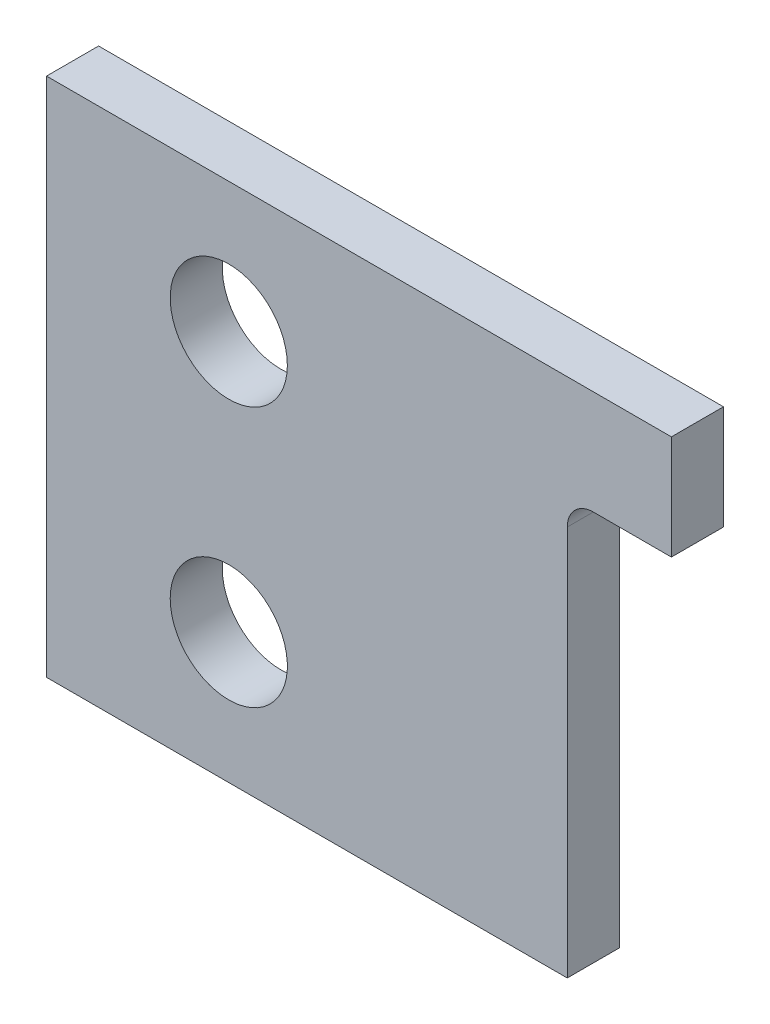
SolidWorks part; units mm, degrees
material "不锈钢"
ref_plane "前基準面" through (0, 0, 0) normal (0, 0, 1) x (1, 0, 0)
ref_plane "上基準面" through (0, 0, 0) normal (0, 1, 0) x (1, 0, 0)
ref_plane "右基準面" through (0, 0, 0) normal (1, 0, 0) x (0, 0, -1)
sketch "草图1" plane through (0, 0, 0) normal (0, 0, 1) x (1, 0, 0)
  line L1 (0, 0) -> (60, 0)
  line L2 (0, 0) -> (0, 20)
  line L3 (0, 20) -> (60, 20)
  line L4 (60, 0) -> (60, 20)
  dimension "D1" = 60
  dimension "D2" = 20
extrude "凸台-拉伸1" add sketch "草图1" along normal blind 2
sketch "草图2" plane through (0, 0, 2) normal (0, 0, 1) x (1, 0, 0)
  line L0 (0, 0) -> (60, 0) construction
  line L1 (20, 0) -> (40, 0)
  line L2 (20, 0) -> (20, 16)
  line L3 (20, 16) -> (40, 16)
  line L4 (40, 0) -> (40, 16)
  line L5 (30, 0) -> (30, 13.6351) construction
  line L6 (60, 20) -> (0, 20) construction
  dimension "D1" = 20
  dimension "D2" = 4
extrude "切除-拉伸1" cut sketch "草图2" against normal through all
fillet "圆角1" radius 1 2 edges at (40, 16, 1) (20, 16, 1)
sketch "草图3" plane through (0, 0, 2) normal (0, 0, 1) x (1, 0, 0)
  line L0 (30, 20) -> (30, 16) construction
  line L1 (60, 20) -> (0, 20) construction
  line L2 (39, 16) -> (21, 16) construction
  line L3 (0, 10) -> (60, 10) construction
  line L4 (0, 20) -> (0, 0) construction
  line L5 (60, 0) -> (60, 20) construction
  circle A0 centre (7, 15) radius 2.25
  circle A1 centre (53, 15) radius 2.25
  circle A2 centre (53, 5) radius 2.25
  circle A3 centre (7, 5) radius 2.25
  dimension "D1" = 4.5
  dimension "D2" = 10
  dimension "D3" = 46
extrude "切除-拉伸2" cut sketch "草图3" against normal through all
sketch "草图4" plane through (0, 0, 2) normal (0, 0, 1) x (1, 0, 0)
  line L0 (60, 20) -> (0, 20) construction
  line L1 (24, 20) -> (60, 20)
  line L2 (24, 20) -> (24, 0)
  line L3 (24, 0) -> (60, 0)
  line L4 (60, 20) -> (60, 0)
  line L5 (0, 20) -> (0, 0) construction
  dimension "D1" = 24
extrude "切除-拉伸3" cut sketch "草图4" against normal blind 10
